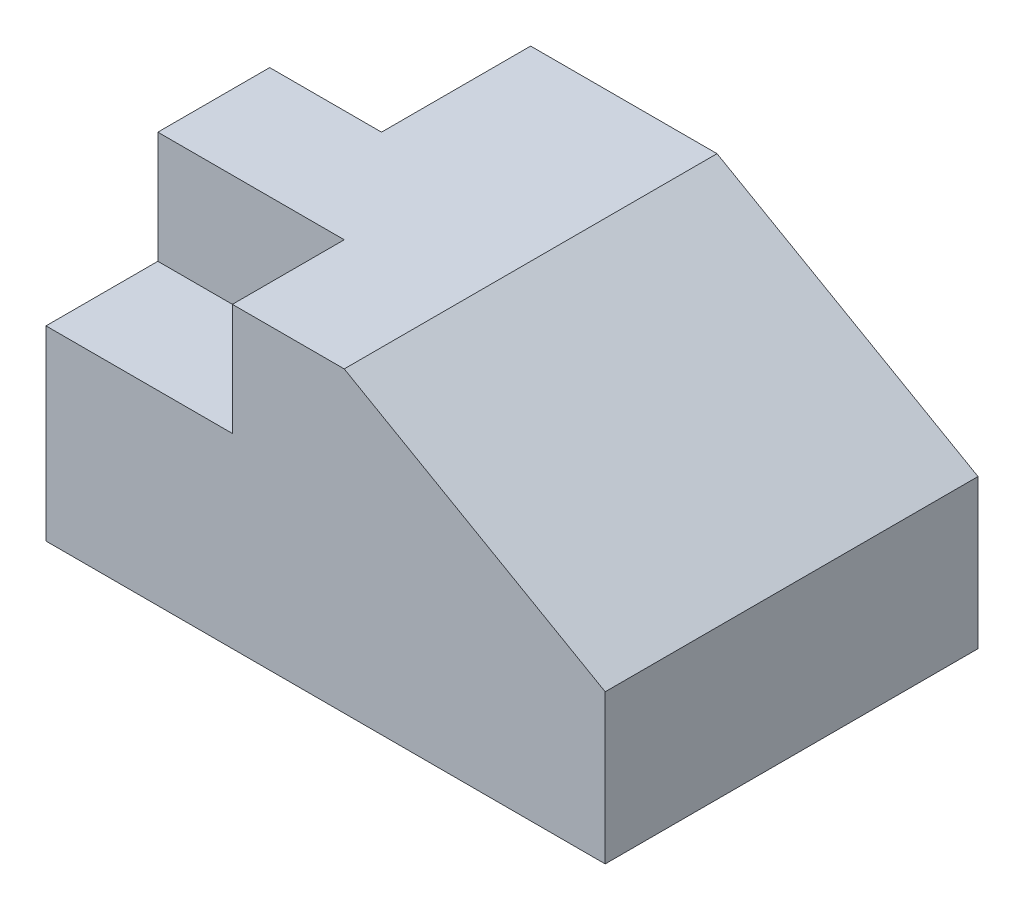
SolidWorks part; units mm, degrees
ref_plane "Front Plane" through (0, 0, 0) normal (0, 0, 1) x (1, 0, 0)
ref_plane "Top Plane" through (0, 0, 0) normal (0, 1, 0) x (1, 0, 0)
ref_plane "Right Plane" through (0, 0, 0) normal (1, 0, 0) x (0, 0, -1)
sketch "Sketch1" plane through (0, 0, 0) normal (0, 0, 1) x (1, 0, 0)
  line L0 (0, 0) -> (0, 80)
  line L1 (0, 80) -> (80, 80)
  line L2 (80, 80) -> (150, 40)
  line L3 (150, 40) -> (150, 0)
  line L4 (150, 0) -> (0, 0)
  line L5 (0, 50) -> (50, 50)
  line L6 (50, 50) -> (50, 80)
  dimension "D1" = 150
  dimension "D2" = 40
  dimension "D3" = 50
  dimension "D4" = 80
  dimension "D5" = 30
  dimension "D6" = 80
extrude "Boss-Extrude1" add sketch "Sketch1" along normal mid plane 100 contours L5 L6 L1 L0 | L6 L5 L0 L4 L3 L2 L1
sketch "Sketch2" plane through (0, 80, 0) normal (0, 1, 0) x (1, 0, 0)
  line L1 (0, 50) -> (30, 50)
  line L2 (0, 50) -> (0, 10)
  line L3 (0, 10) -> (30, 10)
  line L4 (30, 50) -> (30, 10)
  line L5 (0, -50) -> (50, -50)
  line L6 (0, -50) -> (0, -20)
  line L7 (0, -20) -> (50, -20)
  line L8 (50, -50) -> (50, -20)
  dimension "D1" = 40
  dimension "D2" = 30
  dimension "D3" = 50
  dimension "D4" = 30
extrude "Cut-Extrude1" cut sketch "Sketch2" against normal blind 30
